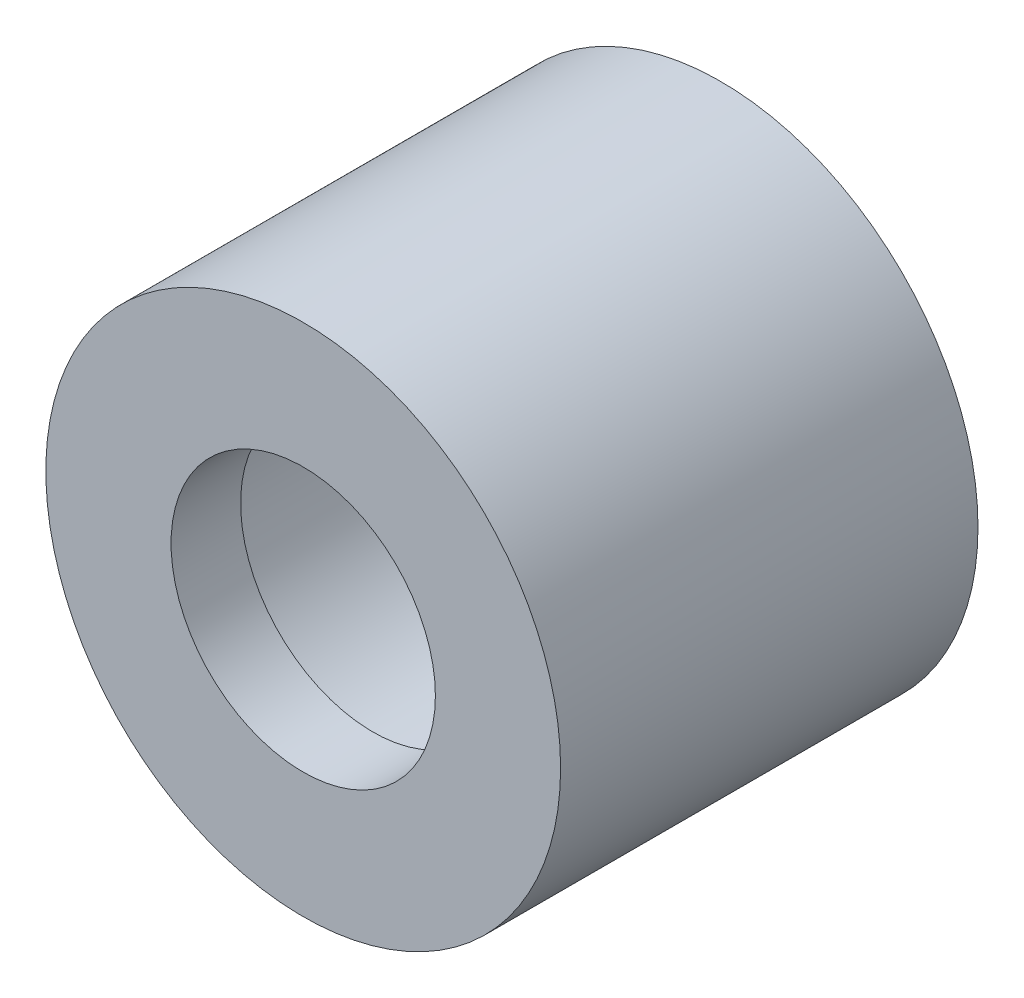
SolidWorks part; units mm, degrees
material "ABS"
ref_plane "Front Plane" through (0, 0, 0) normal (0, 0, 1) x (1, 0, 0)
ref_plane "Top Plane" through (0, 0, 0) normal (0, 1, 0) x (1, 0, 0)
ref_plane "Right Plane" through (0, 0, 0) normal (1, 0, 0) x (0, 0, -1)
sketch "Sketch1" plane through (0, 0, 0) normal (0, 0, 1) x (1, 0, 0)
  circle A0 centre (0, 0) radius 23.495
  circle A1 centre (0, 0) radius 12.065
  dimension "D1" = 46.99
  dimension "D2" = 11.43
extrude "Boss-Extrude1" add sketch "Sketch1" against normal blind 38.1
sketch "Sketch2" plane through (0, 0, -38.1) normal (0, 0, -1) x (-1, 0, 0)
  circle A0 centre (0, 0) radius 12.065 construction
  circle A1 centre (0, 0) radius 12.065
  circle A2 centre (0, 0) radius 15.24
  dimension "D1" = 3.175
extrude "Cut-Extrude1" cut sketch "Sketch2" against normal blind 31.75
sketch "Sketch4" plane through (0, 0, -38.1) normal (0, 0, -1) x (-1, 0, 0)
  line L0 (0, 15.24) -> (0, 23.495) construction
  line L1 (0, -15.24) -> (0, -23.495) construction
  circle A0 centre (0, 19.3675) radius 2.54
  circle A1 centre (0, -19.3675) radius 2.54
  circle A2 centre (0, 0) radius 15.24 construction
  circle A3 centre (0, 0) radius 15.24 construction
  circle A4 centre (0, 0) radius 23.495 construction
  point P8 (0, 15.24)
  point P13 (0, 23.495)
  point P16 (0, 0)
  point P18 (0, -15.24)
  point P19 (0, -23.495)
  point P20 (0, 0)
  dimension "D1" = 5.08
extrude "Cut-Extrude5" cut sketch "Sketch4" against normal blind 5.08
